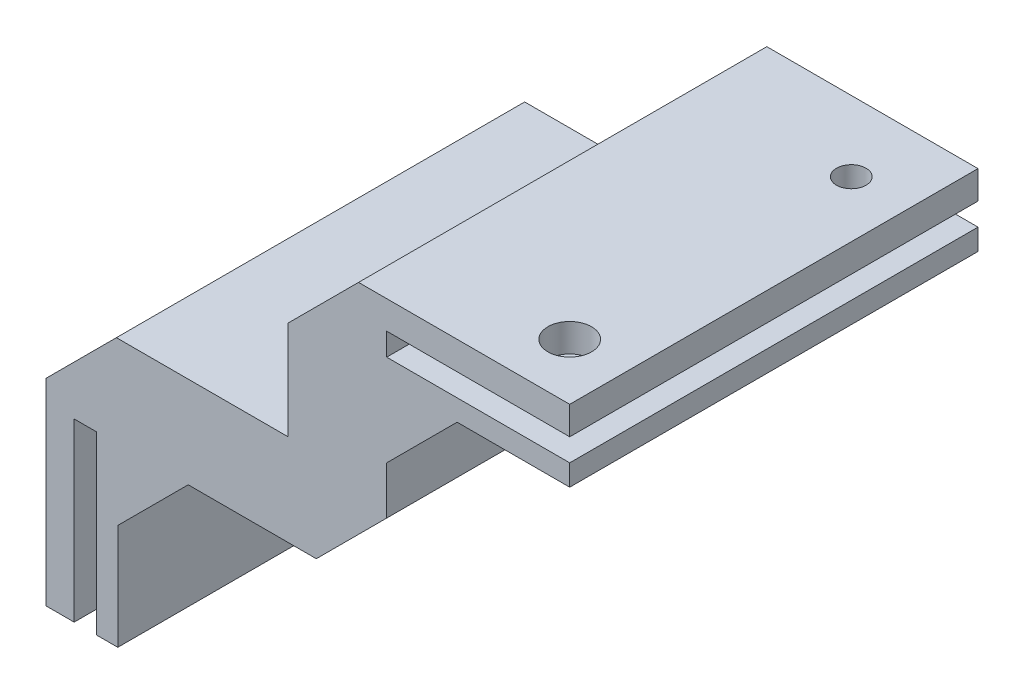
SolidWorks part; units mm, degrees
material "ABS"
ref_plane "Płaszczyzna przednia" through (0, 0, 0) normal (0, 0, 1) x (1, 0, 0)
ref_plane "Płaszczyzna górna" through (0, 0, 0) normal (0, 1, 0) x (1, 0, 0)
ref_plane "Płaszczyzna prawa" through (0, 0, 0) normal (1, 0, 0) x (0, 0, -1)
sketch "Szkic1" plane through (0, 0, 0) normal (0, 0, 1) x (1, 0, 0)
  line L0 (0, 0) -> (-4, 0)
  line L1 (-4, 0) -> (-4, 15)
  line L2 (-4, 15) -> (-7.2, 15)
  line L3 (-7.2, 15) -> (-7.2, 0)
  line L4 (-7.2, 0) -> (-10.2, 0)
  line L5 (-10.2, 0) -> (-10.2, 15)
  line L6 (0, 0) -> (0, 28)
  line L7 (0, 28) -> (-34.4, 28)
  line L8 (-10.2, 15) -> (-38.4, 15)
  line L9 (-34.4, 28) -> (-34.4, 52)
  line L10 (-34.4, 52) -> (-74.4, 52)
  line L11 (-74.4, 52) -> (-74.4, 48)
  line L12 (-74.4, 48) -> (-48.4, 48)
  line L13 (-48.4, 48) -> (-48.4, 44.8)
  line L14 (-48.4, 44.8) -> (-74.4, 44.8)
  line L15 (-74.4, 44.8) -> (-74.4, 41.8)
  line L16 (-74.4, 41.8) -> (-48.4, 41.8)
  line L17 (-48.4, 41.8) -> (-48.4, 25)
  line L18 (-48.4, 25) -> (-38.4, 15)
  dimension "D1" = 4
  dimension "D2" = 3
  dimension "D3" = 3.2
  dimension "D4" = 15
  dimension "D5" = 28
  dimension "D6" = 34.4
  dimension "D7" = 28.2
  dimension "D8" = 4
  dimension "D9" = 3.2
  dimension "D10" = 3
  dimension "D11" = 26
  dimension "D12" = 14
  dimension "D13" = 24
  dimension "D14" = 16.8
extrude "Dodanie-wyciągnięcie1" add sketch "Szkic1" along normal blind 58
chamfer "Sfazowanie1" distance 10 angle 45 4 edges at (-10.2, 15, 29) (-48.4, 41.8, 29) (0, 28, 29) (-34.4, 52, 29)
sketch "Szkic2" plane through (0, 0, 0) normal (0, -1, 0) x (1, 0, 0)
  line L0 (-4, 0) -> (0, 0) construction
  line L1 (0, 0) -> (0, 58) construction
  line L2 (0, 58) -> (-4, 58) construction
  line L3 (-4, 58) -> (-4, 0) construction
  line L4 (-10.2, 0) -> (-7.2, 0) construction
  line L5 (-7.2, 0) -> (-7.2, 58) construction
  line L6 (-7.2, 58) -> (-10.2, 58) construction
  line L7 (-10.2, 58) -> (-10.2, 0) construction
  line L8 (-4, 0) -> (0, 0)
  line L9 (0, 0) -> (0, 58)
  line L10 (0, 58) -> (-4, 58)
  line L11 (-4, 58) -> (-4, 0)
  line L12 (-10.2, 0) -> (-7.2, 0)
  line L13 (-7.2, 0) -> (-7.2, 58)
  line L14 (-7.2, 58) -> (-10.2, 58)
  line L15 (-10.2, 58) -> (-10.2, 0)
extrude "Dodanie-wyciągnięcie2" add sketch "Szkic2" along normal blind 10
sketch "Szkic3" plane through (0, 41.8, 0) normal (0, -1, 0) x (1, 0, 0)
  line L0 (-74.4, 58) -> (-58.4, 58) construction
  line L1 (-74.4, 0) -> (-58.4, 0) construction
  line L2 (-74.4, 58) -> (-74.4, 0) construction
  circle A0 centre (-66.4, 10) radius 2.1
  circle A1 centre (-66.4, 50) radius 3.1
  dimension "D1" = 8
  dimension "D4" = 6.2
  dimension "D5" = 4.2
  dimension "D2" = 10
  dimension "D3" = 8
extrude "Wytnij-wyciągnięcie1" cut sketch "Szkic3" against normal through all contours A0 | A1
sketch "Szkic4" plane through (-10.2, 0, 0) normal (-1, 0, 0) x (0, 0, 1)
  line L0 (58, 5) -> (0, 5) construction
  line L1 (0, 5) -> (0, -10) construction
  circle A0 centre (14, -3) radius 2.1
  dimension "D1" = 4.2
  dimension "D2" = 8
  dimension "D3" = 14
extrude "Wytnij-wyciągnięcie2" cut sketch "Szkic4" against normal through all
mirror "Lustro1" about plane through (-74.4, 52, 58) normal (1, 0, 0) of bodies 107
sketch "Szkic5" plane through (0, 41.8, 0) normal (0, -1, 0) x (1, 0, 0)
  line L1 (-74.4, 0) -> (15.7114, 0)
  line L2 (-74.4, 0) -> (-74.4, 70.9769)
  line L3 (-74.4, 70.9769) -> (15.7114, 70.9769)
  line L4 (15.7114, 0) -> (15.7114, 70.9769)
extrude "Wytnij-wyciągnięcie3" cut sketch "Szkic5" against normal through all and the other way through all
